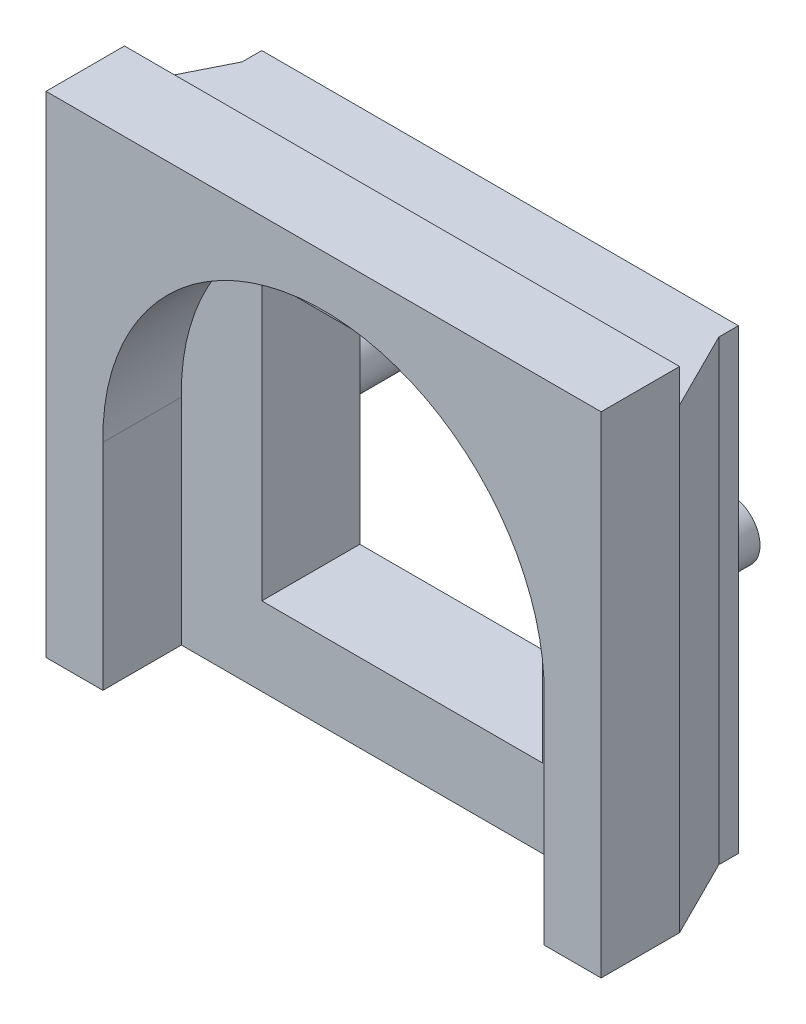
SolidWorks part; units mm, degrees
ref_plane "Front Plane" through (0, 0, 0) normal (0, 0, 1) x (1, 0, 0)
ref_plane "Top Plane" through (0, 0, 0) normal (0, 1, 0) x (1, 0, 0)
ref_plane "Right Plane" through (0, 0, 0) normal (1, 0, 0) x (0, 0, -1)
sketch "Sketch1" plane through (0, 0, 0) normal (0, 0, 1) x (1, 0, 0)
  line L0 (-12.15, 12.15) -> (12.15, 12.15)
  line L1 (-7.15, 7.15) -> (7.15, 7.15)
  line L2 (-7.15, 7.15) -> (-7.15, -7.15)
  line L3 (-7.15, -7.15) -> (7.15, -7.15)
  line L4 (7.15, 7.15) -> (7.15, -7.15)
  line L5 (-7.15, 7.15) -> (7.15, -7.15) construction
  line L6 (-7.15, -7.15) -> (7.15, 7.15) construction
  line L7 (12.15, 12.15) -> (12.15, -12.15)
  line L8 (-12.15, -12.15) -> (12.15, -12.15)
  line L9 (-12.15, 12.15) -> (-12.15, -12.15)
  point P0 (0, 0)
  dimension "D1" = 14.3
  dimension "D2" = 14.3
  dimension "D3" = 5
extrude "Boss-Extrude1" add sketch "Sketch1" along normal blind 4
sketch "Sketch3" plane through (0, 0, 0) normal (0, 0, -1) x (-1, 0, 0)
  line L0 (0, 0) -> (0, 18.9247) construction
  line L1 (7.15, 0) -> (12.15, 0) construction
  line L2 (7.15, 7.15) -> (7.15, -7.15) construction
  line L3 (12.15, 12.15) -> (12.15, -12.15) construction
  circle A0 centre (8.75, 0) radius 1.5
  circle A1 centre (-8.75, 0) radius 1.5
  point P13 (0, 0)
  point P14 (0, 0)
  dimension "D1" = 1.6
extrude "Boss-Extrude4" add sketch "Sketch3" along normal blind 4
sketch "Sketch4" plane through (0, 0, 4) normal (0, 0, 1) x (1, 0, 0)
  line L0 (11.2482, -0.2018) -> (11.2482, -11.15)
  line L1 (-11.2482, -0.2018) -> (-11.2482, -11.15)
  line L2 (-11.2482, -11.15) -> (-14.15, -11.15)
  line L3 (-14.15, -11.15) -> (-14.15, 13.85)
  line L4 (-14.15, 13.85) -> (14.15, 13.85)
  line L5 (11.2482, -11.15) -> (14.15, -11.15)
  line L6 (14.15, -11.15) -> (14.15, 13.85)
  arc A1 (11.2482, -0.2018) -> (-11.2482, -0.2018) centre (0, 0) ccw
extrude "Boss-Extrude5" add sketch "Sketch4" along normal blind 4
sketch "Sketch5" plane through (0, 0, 0) normal (0, 1, 0) x (1, 0, 0)
  line L0 (-12.15, 0) -> (-14.15, -4)
  line L1 (-14.15, -4) -> (-12.15, -4)
  line L2 (-12.15, -4) -> (-12.15, 0)
  line L3 (12.15, 0) -> (12.15, -4)
  line L4 (12.15, -4) -> (14.15, -4)
  line L5 (14.15, -4) -> (12.15, 0)
extrude "Boss-Extrude6" add sketch "Sketch5" along normal up to surface and the other way up to surface up to face at (0, 12.15, 2) other way up to face at (12.5893, -11.15, 5.6)
sketch "Sketch6" plane through (0, 0, 4) normal (0, 0, 1) x (1, 0, 0)
  line L0 (-14.15, -11.15) -> (-17.465, -11.15)
  line L1 (-17.465, -11.15) -> (-17.465, -14.475)
  line L2 (-17.465, -14.475) -> (16.8484, -14.475)
  line L3 (16.8484, -14.475) -> (16.8484, -10.7389)
  line L4 (16.8484, -10.7389) -> (14.15, -11.15)
  line L5 (14.15, -11.15) -> (-14.15, -11.15)
extrude "Cut-Extrude1" cut sketch "Sketch6" against normal blind 11
sketch "Sketch7" plane through (0, 0, 0) normal (0, 0, -1) x (-1, 0, 0)
  line L4 (-7.15, 7.15) -> (7.15, 7.15) construction
  line L5 (-7.15, -7.15) -> (-7.15, 7.15) construction
  line L6 (7.15, -7.15) -> (-7.15, -7.15) construction
  line L7 (7.15, 7.15) -> (7.15, -7.15) construction
  line L8 (-12.15, 12.15) -> (-12.15, -11.15)
  line L9 (-12.15, -11.15) -> (12.15, -11.15)
  line L10 (12.15, -11.15) -> (12.15, 12.15)
  line L11 (12.15, 12.15) -> (-12.15, 12.15)
  line L16 (-12.15, 12.15) -> (-12.15, -11.15)
  line L17 (-12.15, -11.15) -> (12.15, -11.15)
  line L18 (12.15, -11.15) -> (12.15, 12.15)
  line L19 (12.15, 12.15) -> (-12.15, 12.15)
  line L20 (-7.15, 7.15) -> (7.15, 7.15)
  line L21 (-7.15, -7.15) -> (-7.15, 7.15)
  line L22 (7.15, -7.15) -> (-7.15, -7.15)
  line L23 (7.15, 7.15) -> (7.15, -7.15)
  dimension "D1" = 0
extrude "Boss-Extrude8" add sketch "Sketch7" along normal blind 1
